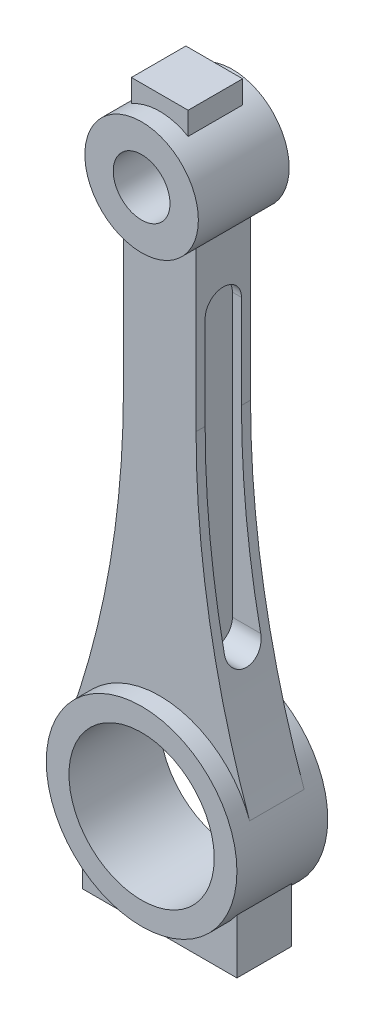
SolidWorks part; units mm, degrees
ref_plane "Front Plane" through (0, 0, 0) normal (0, 0, 1) x (1, 0, 0)
ref_plane "Top Plane" through (0, 0, 0) normal (0, 1, 0) x (1, 0, 0)
ref_plane "Right Plane" through (0, 0, 0) normal (1, 0, 0) x (0, 0, -1)
sketch "Sketch2" plane through (0, 0, 0) normal (0, 0, 1) x (1, 0, 0)
  circle A0 centre (0, 0) radius 21
  circle A1 centre (0, 0) radius 16
  circle A2 centre (0, 120) radius 6.25
  circle A3 centre (0, 120) radius 12.5
  dimension "D1" = 42
  dimension "D2" = 32
  dimension "D3" = 12.5
  dimension "D4" = 25
  dimension "D5" = 120
extrude "Boss-Extrude1" add sketch "Sketch2" along normal mid plane 20
sketch "Sketch3" plane through (0, 0, 0) normal (0, 0, 1) x (1, 0, 0)
  line L0 (-8, 110.3953) -> (-8, 75.3953)
  line L1 (8, 110.3953) -> (8, 75.3953)
  line L2 (0, 120) -> (0, 87.5641) construction
  circle A0 centre (0, 120) radius 12.5 construction
  circle A1 centre (0, 0) radius 21 construction
  arc A2 (-8, 110.3953) -> (8, 110.3953) centre (0, 120) ccw
  arc A3 (19.7874, 7.0327) -> (-19.7874, 7.0327) centre (0, 0) ccw
  arc A4 (8, 75.3953) -> (19.7874, 7.0327) centre (212.1328, 75.3953) ccw
  arc A5 (-8, 75.3953) -> (-19.7874, 7.0327) centre (-212.1328, 75.3953) cw
  point P8 (8, 92.8953)
  dimension "D1" = 8
  dimension "D2" = 35
extrude "Boss-Extrude2" add sketch "Sketch3" along normal mid plane 12
sketch "Sketch4" plane through (0, 0, 0) normal (0, 0, 1) x (1, 0, 0)
  line L0 (0, 137.1136) -> (0, -31.581) construction
  line L1 (-6.25, 135.8253) -> (-6.25, 130.8253)
  line L2 (6.25, 135.8253) -> (6.25, 130.8253)
  line L3 (-6.25, 135.8253) -> (6.25, 135.8253)
  line L4 (-17, -24.3288) -> (-17, -12.3288)
  line L5 (17, -24.3288) -> (17, -12.3288)
  line L6 (-17, -24.3288) -> (17, -24.3288)
  circle A0 centre (0, 120) radius 12.5 construction
  arc A1 (0, 107.5) -> (-6.25, 130.8253) centre (0, 120) ccw
  circle A2 centre (0, 0) radius 21 construction
  arc A3 (-17, -12.3288) -> (17, -12.3288) centre (0, 0) ccw
  dimension "D1" = 5
  dimension "D2" = 12.5
  dimension "D3" = 12
  dimension "D4" = 34
extrude "Boss-Extrude3" add sketch "Sketch4" along normal mid plane 12 contours L0 L3 L1 A1 | L3 L0 A1 L2 | A3 L5 L6 L4
ref_plane "Plane1" through (6, 0, 0) normal (1, 0, 0) x (0, 0, -1)
sketch "Sketch5" plane through (6, 0, 0) normal (1, 0, 0) x (0, 0, -1)
  line L0 (0, 96) -> (0, 34) construction
  line L1 (4, 96) -> (4, 34)
  line L2 (-4, 96) -> (-4, 34)
  line L3 (-10, 120) -> (10, 120) construction
  line L4 (-10, 132.5) -> (-10, 107.5) construction
  line L5 (10, 107.5) -> (10, 132.5) construction
  arc A0 (4, 96) -> (-4, 96) centre (0, 96) ccw
  arc A1 (-4, 34) -> (4, 34) centre (0, 34) ccw
  point P3 (0, 65)
  point P8 (0, 120)
  point P15 (0, 100)
  dimension "D1" = 4
  dimension "D2" = 62
  dimension "D3" = 20
extrude "Cut-Extrude1" cut sketch "Sketch5" along normal blind 62
mirror "Mirror1" about plane through (0, 0, 0) normal (1, 0, 0) of "Cut-Extrude1"
